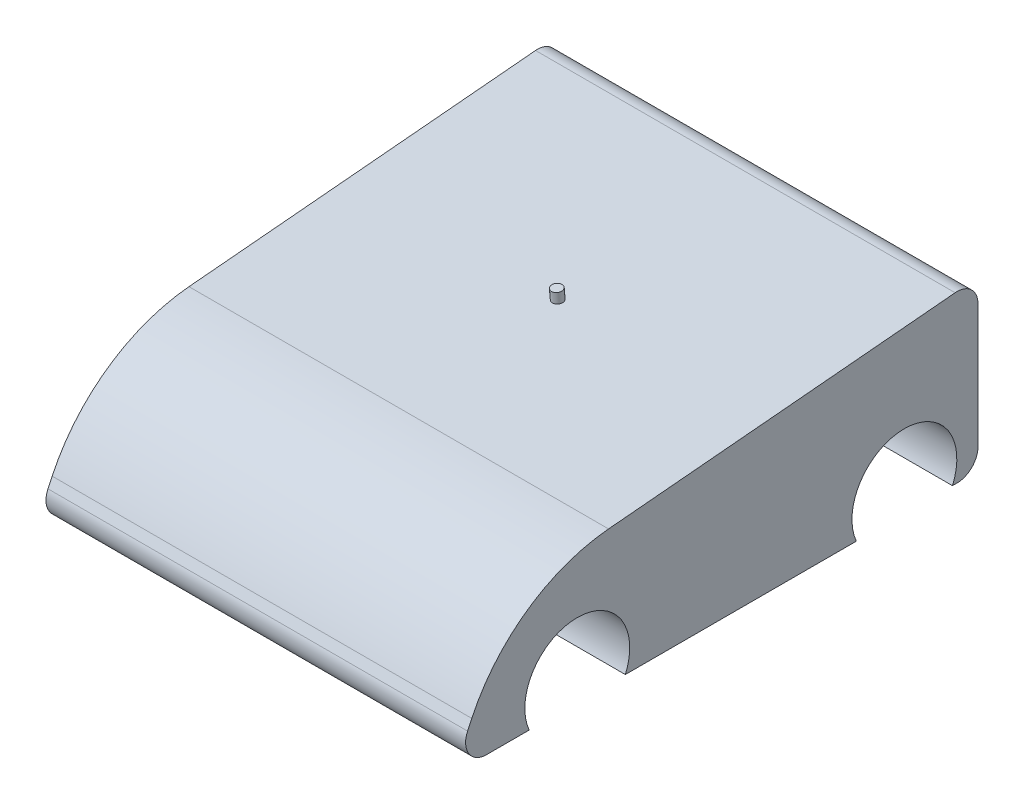
SolidWorks part; units mm, degrees
ref_plane "Front Plane" through (0, 0, 0) normal (0, 0, 1) x (1, 0, 0)
ref_plane "Top Plane" through (0, 0, 0) normal (0, 1, 0) x (1, 0, 0)
ref_plane "Right Plane" through (0, 0, 0) normal (1, 0, 0) x (0, 0, -1)
sketch "Sketch2" plane through (0, 0, 0) normal (1, 0, 0) x (0, 0, -1)
  line L0 (-112.6439, 14.2578) -> (-110.6453, 18.5051)
  line L1 (-45.4449, 64.1191) -> (119.7486, 79.0171)
  line L2 (130.6468, 69.0576) -> (130.6468, 10)
  line L3 (120.6468, 0) -> (-103.5956, 0)
  arc A0 (-110.6453, 18.5051) -> (-45.4449, 64.1191) centre (-38.2592, -15.5575) cw
  arc A1 (-112.6439, 14.2578) -> (-103.5956, 0) centre (-103.5956, 10) ccw
  arc A2 (130.6468, 10) -> (120.6468, 0) centre (120.6468, 10) cw
  arc A3 (119.7486, 79.0171) -> (130.6468, 69.0576) centre (120.6468, 69.0576) cw
  point P6 (-91.1191, 60)
  point P9 (-119.3532, 0)
  point P12 (130.6468, 0)
  point P15 (130.6468, 80)
  dimension "D4" = 80
  dimension "D5" = 10
  dimension "D6" = 10
  dimension "D1" = 250
  dimension "D2" = 80
  dimension "D3" = 60
extrude "Boss-Extrude1" add sketch "Sketch2" along normal mid plane 200
sketch "Sketch3" plane through (100, 0, 0) normal (1, 0, 0) x (0, 0, -1)
  line L0 (-103.5956, 0) -> (120.6468, 0) construction
  circle A0 centre (-60.3575, 10) radius 25
  circle A1 centre (95.5617, 10) radius 25
  dimension "D1" = 50
  dimension "D2" = 10
  dimension "D3" = 10
extrude "Cut-Extrude1" cut sketch "Sketch3" against normal blind 50
mirror "Mirror1" about plane through (0, 0, 0) normal (1, 0, 0) of "Cut-Extrude1"
sketch "Sketch4" plane through (0, 67.6672, 6.1026) normal (0, 0.996, 0.0898) x (1, 0, 0)
  circle A0 centre (0, 36.5744) radius 2.5
  dimension "D1" = 5
extrude "Boss-Extrude2" add sketch "Sketch4" along normal blind 5
